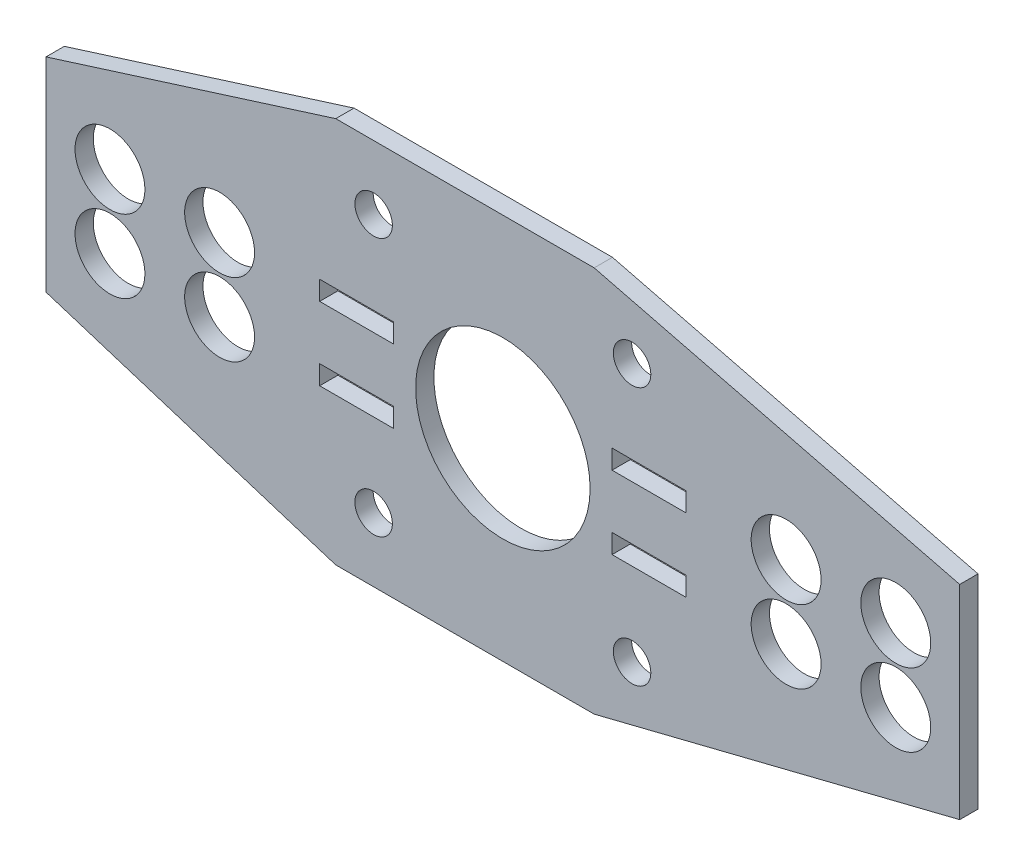
SolidWorks part; units mm, degrees
ref_plane "前视基准面" through (0, 0, 0) normal (0, 0, 1) x (1, 0, 0)
ref_plane "上视基准面" through (0, 0, 0) normal (0, 1, 0) x (1, 0, 0)
ref_plane "右视基准面" through (0, 0, 0) normal (1, 0, 0) x (0, 0, -1)
sketch "草图1" plane through (0, 0, 0) normal (0, 0, 1) x (1, 0, 0)
  line L0 (0, 0) -> (0, -8) construction
  line L1 (0, 0) -> (15, 0)
  line L2 (0, 0) -> (62, 0) construction
  line L3 (19.05, -1.05) -> (10.95, -1.05)
  line L4 (19.05, -1.05) -> (19.05, 1.05)
  line L5 (19.05, 1.05) -> (10.95, 1.05)
  line L6 (10.95, -1.05) -> (10.95, 1.05)
  line L7 (19.05, -1.05) -> (10.95, 1.05) construction
  line L8 (19.05, 1.05) -> (10.95, -1.05) construction
  line L9 (31, 0) -> (31, -4) construction
  line L10 (42.95, -1.05) -> (51.05, -1.05)
  line L11 (42.95, -1.05) -> (42.95, 1.05)
  line L12 (51.05, -1.05) -> (51.05, 1.05)
  line L13 (42.95, 1.05) -> (51.05, 1.05)
  line L14 (0, -4) -> (2.5207, -4) construction
  line L15 (51.05, -6.95) -> (51.05, -9.05)
  line L16 (42.95, -6.95) -> (42.95, -9.05)
  line L17 (42.95, -9.05) -> (51.05, -9.05)
  line L18 (42.95, -6.95) -> (51.05, -6.95)
  line L19 (19.05, -6.95) -> (19.05, -9.05)
  line L20 (10.95, -6.95) -> (10.95, -9.05)
  line L21 (19.05, -6.95) -> (10.95, -6.95)
  line L22 (19.05, -9.05) -> (10.95, -9.05)
  line L23 (31, -4) -> (31, 30.555) construction
  line L24 (81, -15.1497) -> (-19, -15.1497) construction
  line L25 (81, -15.1497) -> (81, 7.1497)
  line L26 (81, 7.1497) -> (-19, 7.1497) construction
  line L27 (-19, -15.1497) -> (-19, 7.1497)
  line L28 (81, -15.1497) -> (-19, 7.1497) construction
  line L29 (81, 7.1497) -> (-19, -15.1497) construction
  line L30 (31, -4) -> (54.6995, 19.6995) construction
  line L31 (-19, 7.1497) -> (12.7087, 17.1497)
  line L32 (12.7087, 17.1497) -> (40.993, 17.1497)
  line L33 (40.993, 17.1497) -> (81, 7.1497)
  line L34 (31, -4) -> (84.8449, -4) construction
  line L35 (12.7087, -25.1497) -> (40.993, -25.1497)
  line L36 (40.993, -25.1497) -> (81, -15.1497)
  line L37 (-19, -15.1497) -> (12.7087, -25.1497)
  line L38 (62, 0) -> (74, 0) construction
  circle A0 centre (0, 0) radius 3.825
  circle A1 centre (62, 0) radius 3.825
  circle A2 centre (62, -8) radius 3.825
  circle A3 centre (0, -8) radius 3.825
  circle A5 centre (31, -4) radius 20 construction
  circle A6 centre (45.1421, 10.1421) radius 2.05
  circle A7 centre (45.1421, -18.1421) radius 2.05
  circle A8 centre (16.8579, -18.1421) radius 2.05
  circle A9 centre (16.8579, 10.1421) radius 2.05
  circle A11 centre (74, 0) radius 3.825
  circle A12 centre (74, -8) radius 3.825
  circle A13 centre (-12, -8) radius 3.825
  circle A14 centre (-12, 0) radius 3.825
  circle A15 centre (31, -4) radius 9.55
  dimension "D2" = 7.65
  dimension "D8" = 4
  dimension "D10" = 12
  dimension "D12" = 7.65
  dimension "D13" = 19.1
  dimension "D1" = 8
  dimension "D3" = 15
  dimension "D4" = 8.1
  dimension "D5" = 2.1
  dimension "D6" = 62
  dimension "D7" = 45
  dimension "D9" = 10
  dimension "D11" = 100
extrude "凸台-拉伸1" add sketch "草图1" along normal blind 2
